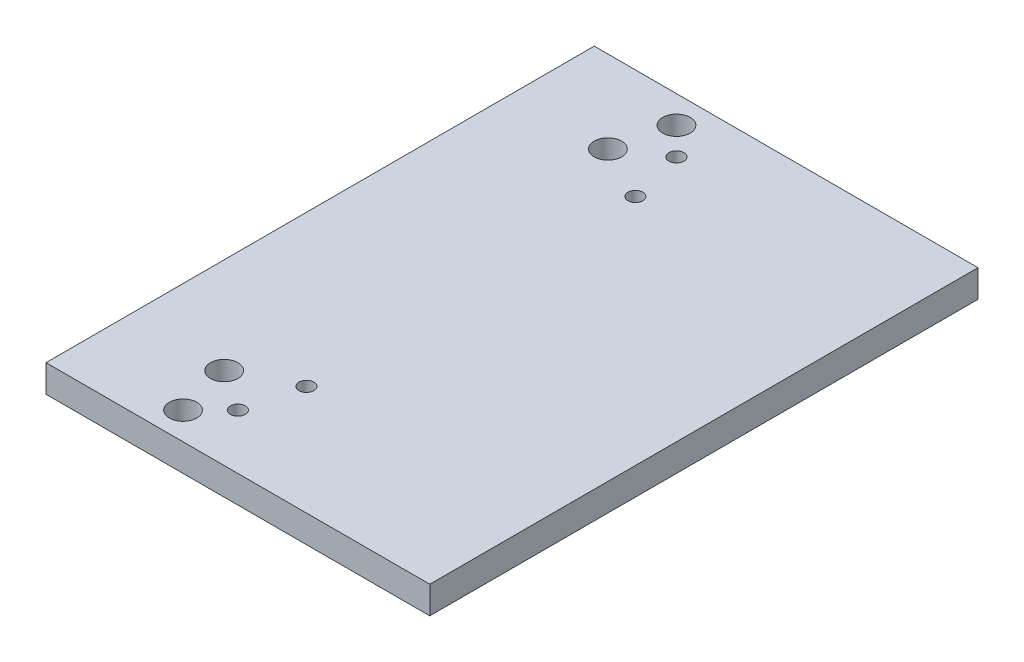
SolidWorks part; units mm, degrees
ref_plane "Front" through (0, 0, 0) normal (0, 0, 1) x (1, 0, 0)
ref_plane "Top" through (0, 0, 0) normal (0, 1, 0) x (1, 0, 0)
ref_plane "Right" through (0, 0, 0) normal (1, 0, 0) x (0, 0, -1)
sketch "Sketch1" plane through (0, 0, 0) normal (0, 1, 0) x (1, 0, 0)
  line L1 (-44.45, -63.5) -> (44.45, -63.5)
  line L2 (-44.45, -63.5) -> (-44.45, 63.5)
  line L3 (-44.45, 63.5) -> (44.45, 63.5)
  line L4 (44.45, -63.5) -> (44.45, 63.5)
  line L5 (-44.45, -63.5) -> (44.45, 63.5) construction
  line L6 (-44.45, 63.5) -> (44.45, -63.5) construction
  point P0 (0, 0)
  dimension "D1" = 127
  dimension "D2" = 88.9
extrude "Boss-Extrude1" add sketch "Sketch1" along normal blind 6.35 contours L3 L4 L1 L2
sketch "Sketch2" plane through (0, 6.35, 0) normal (0, 1, 0) x (1, 0, 0)
  point P0 (-22.225, -44.45)
  point P1 (-22.225, 44.45)
hole_wizard "1/4 (0.2500) Dowel Hole1" positions "Sketch3" profile "Sketch4" hole size "1/4" standard "ANSI Inch" end condition up to next
sketch "Sketch3" plane through (0, 6.35, 0) normal (0, 1, 0) x (1, 0, 0)
  point P0 (-22.225, -44.45)
  point P3 (-22.225, 44.45)
sketch "Sketch4" plane through (-22.225, 6.35, 44.45) normal (1, 0, 0) x (0, 0, 1)
  line L0 (0, 0) -> (0, 6.35)
  line L1 (0, 6.35) -> (3.175, 6.35)
  line L2 (3.175, 6.35) -> (3.175, 0)
  line L5 (3.175, 0) -> (0, 0)
  line L11 (0, -6.35) -> (0, 107.95) construction
  dimension "Thru Hole Dia." = 6.35
  dimension "Thru Hole Depth" = 6.35
sketch "Sketch5" plane through (0, 6.35, 0) normal (0, 1, 0) x (1, 0, 0)
  point P0 (-9.525, -38.1)
  point P1 (-9.525, 38.1)
hole_wizard "#8-32 Tapped Hole1" positions "Sketch6" profile "Sketch8" tap size "#8-32" standard "ANSI Inch" end condition up to next
sketch "Sketch6" plane through (0, 6.35, 0) normal (0, 1, 0) x (1, 0, 0)
  point P0 (-9.525, -38.1)
  point P3 (-9.525, 38.1)
sketch "Sketch8" plane through (-9.525, 6.35, 38.1) normal (1, 0, 0) x (0, 0, 1)
  line L0 (0, 0) -> (0, 6.35)
  line L1 (0, 6.35) -> (1.7272, 6.35)
  line L2 (1.7272, 6.35) -> (1.7272, 0)
  line L5 (1.7272, 0) -> (0, 0)
  line L11 (0, -6.35) -> (0, 107.95) construction
  dimension "Thru Tap Drill Dia." = 3.4544
  dimension "Thru Tap Drill Depth" = 6.35
cosmetic thread "Hole Thread7"
cosmetic thread "Hole Thread8"
sketch "Sketch9" plane through (0, 6.35, 0) normal (0, 1, 0) x (1, 0, 0)
  point P0 (-19.05, 57.15)
  point P1 (-19.05, -57.15)
hole_wizard "1/4 (0.2500) Dowel Hole2" positions "Sketch10" profile "Sketch12" hole size "1/4" standard "ANSI Inch" end condition through all
sketch "Sketch10" plane through (0, 6.35, 0) normal (0, 1, 0) x (1, 0, 0)
  point P0 (-19.05, 57.15)
  point P3 (-19.05, -57.15)
sketch "Sketch12" plane through (-19.05, 6.35, -57.15) normal (1, 0, 0) x (0, 0, 1)
  line L0 (0, 0) -> (0, 6.35)
  line L1 (0, 6.35) -> (3.175, 6.35)
  line L2 (3.175, 6.35) -> (3.175, 0)
  line L5 (3.175, 0) -> (0, 0)
  line L11 (0, -6.35) -> (0, 107.95) construction
  dimension "Thru Hole Dia." = 6.35
  dimension "Thru Hole Depth" = 6.35
sketch "Sketch13" plane through (0, 6.35, 0) normal (0, 1, 0) x (1, 0, 0)
  point P0 (-12.7, 50.8)
  point P1 (-12.7, -50.8)
hole_wizard "#8-32 Tapped Hole2" positions "Sketch14" profile "Sketch16" tap size "#8-32" standard "ANSI Inch" end condition through all
sketch "Sketch14" plane through (0, 6.35, 0) normal (0, 1, 0) x (1, 0, 0)
  point P0 (-12.7, 50.8)
  point P3 (-12.7, -50.8)
sketch "Sketch16" plane through (-12.7, 6.35, -50.8) normal (1, 0, 0) x (0, 0, 1)
  line L0 (0, 0) -> (0, 6.35)
  line L1 (0, 6.35) -> (1.7272, 6.35)
  line L2 (1.7272, 6.35) -> (1.7272, 0)
  line L5 (1.7272, 0) -> (0, 0)
  line L11 (0, -6.35) -> (0, 107.95) construction
  dimension "Thru Tap Drill Dia." = 3.4544
  dimension "Thru Tap Drill Depth" = 6.35
cosmetic thread "Hole Thread9"
cosmetic thread "Hole Thread10"
